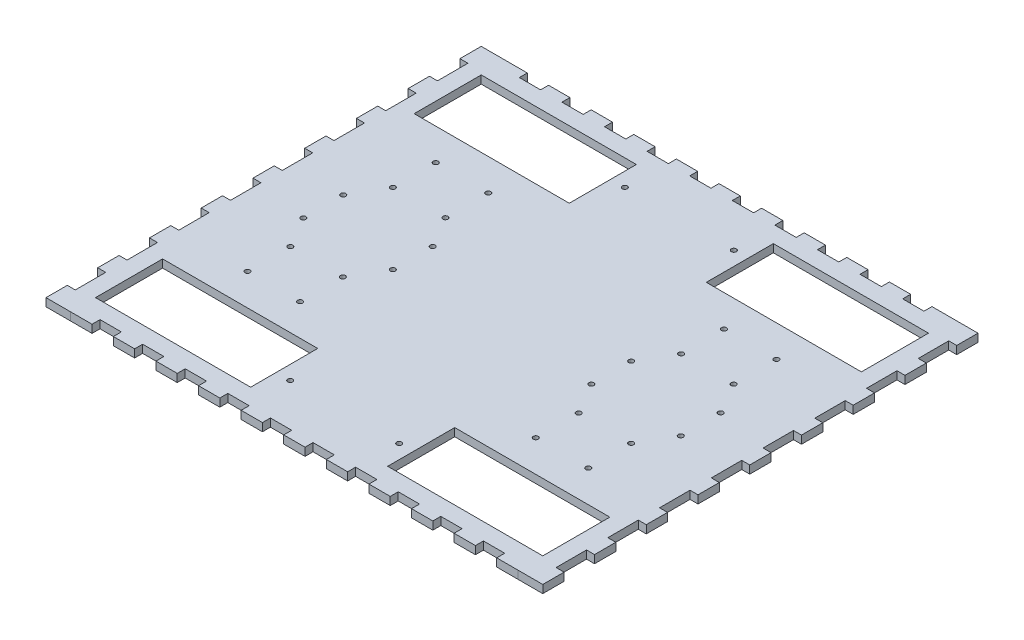
SolidWorks part; units mm, degrees
ref_plane "Front Plane" through (0, 0, 0) normal (0, 0, 1) x (1, 0, 0)
ref_plane "Top Plane" through (0, 0, 0) normal (0, 1, 0) x (1, 0, 0)
ref_plane "Right Plane" through (0, 0, 0) normal (1, 0, 0) x (0, 0, -1)
sketch "Sketch2" plane through (0, 0, 0) normal (0, 1, 0) x (1, 0, 0)
  line L11 (25.4, 125) -> (25.4, 129.7625)
  line L12 (12.7, -125) -> (25.4, -125)
  line L23 (0, -125) -> (0, 125)
  line L24 (12.7, 125) -> (25.4, 125)
  line L29 (266.7, -125) -> (266.7, 125)
  line L30 (25.4, 129.7625) -> (38.1, 129.7625)
  line L35 (38.1, 125) -> (38.1, 129.7625)
  line L41 (0, 125) -> (0, 129.7625)
  line L42 (0, 129.7625) -> (12.7, 129.7625)
  line L47 (12.7, 125) -> (12.7, 129.7625)
  line L48 (50.8, 125) -> (50.8, 129.7625)
  line L53 (50.8, 129.7625) -> (63.5, 129.7625)
  line L54 (63.5, 125) -> (63.5, 129.7625)
  line L59 (76.2, 125) -> (76.2, 129.7625)
  line L60 (76.2, 129.7625) -> (88.9, 129.7625)
  line L65 (88.9, 125) -> (88.9, 129.7625)
  line L66 (101.6, 125) -> (101.6, 129.7625)
  line L71 (101.6, 129.7625) -> (114.3, 129.7625)
  line L72 (114.3, 125) -> (114.3, 129.7625)
  line L77 (127, 125) -> (127, 129.7625)
  line L78 (127, 129.7625) -> (139.7, 129.7625)
  line L79 (139.7, 125) -> (139.7, 129.7625)
  line L80 (152.4, 125) -> (152.4, 129.7625)
  line L81 (152.4, 129.7625) -> (165.1, 129.7625)
  line L82 (165.1, 125) -> (165.1, 129.7625)
  line L83 (177.8, 125) -> (177.8, 129.7625)
  line L84 (177.8, 129.7625) -> (190.5, 129.7625)
  line L85 (190.5, 125) -> (190.5, 129.7625)
  line L86 (203.2, 125) -> (203.2, 129.7625)
  line L87 (203.2, 129.7625) -> (215.9, 129.7625)
  line L88 (215.9, 125) -> (215.9, 129.7625)
  line L89 (228.6, 125) -> (228.6, 129.7625)
  line L90 (228.6, 129.7625) -> (241.3, 129.7625)
  line L91 (241.3, 125) -> (241.3, 129.7625)
  line L92 (254, 125) -> (254, 129.7625)
  line L93 (254, 129.7625) -> (266.7, 129.7625)
  line L94 (266.7, 125) -> (266.7, 129.7625)
  line L95 (38.1, 125) -> (50.8, 125)
  line L96 (63.5, 125) -> (76.2, 125)
  line L97 (88.9, 125) -> (101.6, 125)
  line L98 (114.3, 125) -> (127, 125)
  line L99 (139.7, 125) -> (152.4, 125)
  line L100 (165.1, 125) -> (177.8, 125)
  line L101 (190.5, 125) -> (203.2, 125)
  line L102 (215.9, 125) -> (228.6, 125)
  line L103 (241.3, 125) -> (254, 125)
  line L104 (0, 0) -> (266.7, 0) construction
  line L105 (241.3, -125) -> (254, -125)
  line L106 (215.9, -125) -> (228.6, -125)
  line L107 (190.5, -125) -> (203.2, -125)
  line L108 (165.1, -125) -> (177.8, -125)
  line L109 (139.7, -125) -> (152.4, -125)
  line L110 (114.3, -125) -> (127, -125)
  line L111 (88.9, -125) -> (101.6, -125)
  line L112 (63.5, -125) -> (76.2, -125)
  line L113 (38.1, -125) -> (50.8, -125)
  line L114 (266.7, -125) -> (266.7, -129.7625)
  line L115 (254, -129.7625) -> (266.7, -129.7625)
  line L116 (254, -125) -> (254, -129.7625)
  line L117 (241.3, -125) -> (241.3, -129.7625)
  line L118 (228.6, -129.7625) -> (241.3, -129.7625)
  line L119 (228.6, -125) -> (228.6, -129.7625)
  line L120 (215.9, -125) -> (215.9, -129.7625)
  line L121 (203.2, -129.7625) -> (215.9, -129.7625)
  line L122 (203.2, -125) -> (203.2, -129.7625)
  line L123 (190.5, -125) -> (190.5, -129.7625)
  line L124 (177.8, -129.7625) -> (190.5, -129.7625)
  line L125 (177.8, -125) -> (177.8, -129.7625)
  line L126 (165.1, -125) -> (165.1, -129.7625)
  line L127 (152.4, -129.7625) -> (165.1, -129.7625)
  line L128 (152.4, -125) -> (152.4, -129.7625)
  line L129 (139.7, -125) -> (139.7, -129.7625)
  line L130 (127, -129.7625) -> (139.7, -129.7625)
  line L131 (127, -125) -> (127, -129.7625)
  line L132 (114.3, -125) -> (114.3, -129.7625)
  line L133 (101.6, -129.7625) -> (114.3, -129.7625)
  line L134 (101.6, -125) -> (101.6, -129.7625)
  line L135 (88.9, -125) -> (88.9, -129.7625)
  line L136 (76.2, -129.7625) -> (88.9, -129.7625)
  line L137 (76.2, -125) -> (76.2, -129.7625)
  line L138 (63.5, -125) -> (63.5, -129.7625)
  line L139 (50.8, -129.7625) -> (63.5, -129.7625)
  line L140 (50.8, -125) -> (50.8, -129.7625)
  line L141 (12.7, -125) -> (12.7, -129.7625)
  line L142 (0, -129.7625) -> (12.7, -129.7625)
  line L143 (0, -125) -> (0, -129.7625)
  line L144 (38.1, -125) -> (38.1, -129.7625)
  line L145 (25.4, -129.7625) -> (38.1, -129.7625)
  line L146 (12.7, -125) -> (25.4, -125)
  line L147 (25.4, -125) -> (25.4, -129.7625)
  line L148 (38.1, -125) -> (50.8, -125)
  line L149 (63.5, -125) -> (76.2, -125)
  line L150 (88.9, -125) -> (101.6, -125)
  line L151 (114.3, -125) -> (127, -125)
  line L152 (139.7, -125) -> (152.4, -125)
  line L153 (165.1, -125) -> (177.8, -125)
  line L154 (190.5, -125) -> (203.2, -125)
  line L155 (215.9, -125) -> (228.6, -125)
  line L156 (241.3, -125) -> (254, -125)
  point P68 (0, -129.7625)
  dimension "D1" = 250
  dimension "D2" = 266.7
  dimension "D3" = 12.7
  dimension "D4" = 4.7625
extrude "Boss-Extrude1" add sketch "Sketch2" along normal blind 4.7625 contours L12 L147 L145 L144 L113 L140 L139 L138 L112 L137 L136 L135 L111 L134 L133 L132 L110 L131 L130 L129 L109 L128 L127 L126 L108 L125 L124 L123 L107 L122 L121 L120 L106 L119 L118 L117 L105 L116 L115 L114 L29 L94 L93 L92 L103 L91 L90 L89 L102 L88 L87 | L23 L104 L29 L94 L93 L92 L103 L91 L90 L89 L102 L88 L87 L86 L101 L85 L84 L83 L100 L82 L81 L80 L99 L79 L78 L77 L98 L72 L71 L66 L97 L65 L60 L59 L96 L54 L53 L48 L95 L35 L30 L11 L24 L47 L42 L41
sketch "Sketch5" plane through (0, 4.7625, 0) normal (0, 1, 0) x (1, 0, 0)
  line L0 (100.85, 99.7625) -> (165.85, 99.7625) construction
  line L1 (25.4, 129.7625) -> (38.1, 129.7625) construction
  line L2 (100.85, -99.7625) -> (165.85, -99.7625) construction
  line L4 (127, 129.7625) -> (139.7, 129.7625) construction
  line L5 (0, 0) -> (266.7, 0) construction
  line L6 (0, -129.7625) -> (0, 129.7625) construction
  line L7 (266.7, 129.7625) -> (266.7, -129.7625) construction
  circle A0 centre (31.75, 56.1125) radius 1.5
  circle A1 centre (63.07, 56.1125) radius 1.5
  circle A2 centre (63.07, 30.5625) radius 1.5
  circle A3 centre (31.75, 30.5625) radius 1.5
  circle A20 centre (203.63, 56.1125) radius 1.5
  circle A21 centre (203.63, 30.5625) radius 1.5
  circle A22 centre (234.95, 30.5625) radius 1.5
  circle A23 centre (234.95, 56.1125) radius 1.5
  circle A24 centre (234.95, -56.1125) radius 1.5
  circle A25 centre (234.95, -30.5625) radius 1.5
  circle A26 centre (203.63, -30.5625) radius 1.5
  circle A27 centre (203.63, -56.1125) radius 1.5
  circle A28 centre (31.75, -30.5625) radius 1.5
  circle A29 centre (63.07, -30.5625) radius 1.5
  circle A30 centre (63.07, -56.1125) radius 1.5
  circle A31 centre (31.75, -56.1125) radius 1.5
  circle A32 centre (20.83, 11.885) radius 1.5
  circle A33 centre (74.17, 11.885) radius 1.5
  circle A34 centre (192.53, 11.885) radius 1.5
  circle A35 centre (245.87, 11.885) radius 1.5
  circle A36 centre (245.87, -11.885) radius 1.5
  circle A37 centre (192.53, -11.885) radius 1.5
  circle A38 centre (74.17, -11.885) radius 1.5
  circle A39 centre (20.83, -11.885) radius 1.5
  circle A40 centre (100.85, 99.7625) radius 1.5
  circle A41 centre (165.85, 99.7625) radius 1.5
  circle A42 centre (165.85, -99.7625) radius 1.5
  circle A43 centre (100.85, -99.7625) radius 1.5
  point P3 (64.57, 56.1125)
  point P7 (30.25, 56.1125)
  point P23 (31.75, 129.7625)
  point P50 (31.75, 57.6125)
  point P51 (31.75, 29.0625)
  point P69 (133.35, 99.7625)
  point P70 (133.35, 0)
  dimension "D1" = 28.55
  dimension "D3" = 3
  dimension "D4" = 2
  dimension "D12" = 3
  dimension "D2" = 18.6775
  dimension "D5" = 34.32
  dimension "D6" = 31.75
  dimension "D7" = 20.83
  dimension "D8" = 53.34
  dimension "D9" = 11.885
  dimension "D11" = 20.83
  dimension "D13" = 65
  dimension "D14" = 133.35
  dimension "D15" = 30
  dimension "D10" = 2
extrude "Cut-Extrude1" cut sketch "Sketch5" against normal through all
sketch "Sketch7" plane through (0, 4.7625, 0) normal (0, 1, 0) x (1, 0, 0)
  line L0 (0, 75) -> (92.5, 75)
  line L1 (0, -129.7625) -> (0, 129.7625) construction
  line L2 (92.5, 75) -> (92.5, 115)
  line L3 (92.5, 115) -> (0, 115)
  line L4 (0, 115) -> (0, 75)
  line L5 (0, 0) -> (266.7, 0) construction
  line L6 (266.7, 129.7625) -> (266.7, -129.7625) construction
  line L7 (133.35, 0) -> (133.35, 129.7625) construction
  line L8 (127, 129.7625) -> (139.7, 129.7625) construction
  line L9 (266.7, 115) -> (266.7, 75)
  line L10 (174.2, 115) -> (266.7, 115)
  line L11 (174.2, 75) -> (174.2, 115)
  line L12 (266.7, 75) -> (174.2, 75)
  line L13 (0, -115) -> (0, -75)
  line L14 (92.5, -115) -> (0, -115)
  line L15 (92.5, -75) -> (92.5, -115)
  line L16 (0, -75) -> (92.5, -75)
  line L17 (266.7, -75) -> (174.2, -75)
  line L18 (174.2, -75) -> (174.2, -115)
  line L19 (174.2, -115) -> (266.7, -115)
  line L20 (266.7, -115) -> (266.7, -75)
  dimension "D1" = 40
  dimension "D2" = 75
  dimension "D3" = 92.5
extrude "Cut-Extrude2" cut sketch "Sketch7" against normal through all
sketch "Sketch6" plane through (0, 4.7625, 0) normal (0, 1, 0) x (1, 0, 0)
  line L0 (0, -129.7625) -> (0, -115) construction
  line L1 (0, 129.7625) -> (12.7, 129.7625) construction
  line L2 (0, -75) -> (0, 75) construction
  text T0 "TREY MADE THIS CHASSIS\r\n the robot will be on this\r\n<i>      -\"Danny Devito\"</i>"
  text T1 "Calvin contributed"
  point P5 (106.6973, -5.2225)
  dimension "D1" = 101.6
  dimension "D2" = 82.677
  dimension "D3" = 106.6973
  dimension "D4" = 134.985
sketch "Sketch8" plane through (0, 4.7625, 0) normal (0, 1, 0) x (1, 0, 0)
  line L0 (0, -129.7625) -> (0, -115) construction
  line L1 (0, -129.76) -> (-10, -129.76)
  line L2 (0, -129.76) -> (0, 129.76)
  line L3 (0, 129.76) -> (-10, 129.76)
  line L4 (-10, -117.06) -> (-10, -98.9075)
  line L10 (-14.76, 98.9075) -> (-14.76, 86.2075)
  line L11 (-10, 129.76) -> (-14.76, 129.76)
  line L13 (-10, 117.06) -> (-14.76, 117.06)
  line L14 (-14.76, 129.76) -> (-14.76, 117.06)
  line L15 (-10, 86.2075) -> (-14.76, 86.2075)
  line L16 (-10, 98.9075) -> (-14.76, 98.9075)
  line L17 (-14.76, 68.055) -> (-14.76, 55.355)
  line L18 (-10, 55.355) -> (-14.76, 55.355)
  line L19 (-10, 68.055) -> (-14.76, 68.055)
  line L20 (-14.76, 37.2025) -> (-14.76, 24.5025)
  line L21 (-10, 24.5025) -> (-14.76, 24.5025)
  line L22 (-10, 37.2025) -> (-14.76, 37.2025)
  line L23 (-14.76, 6.35) -> (-14.76, -6.35)
  line L24 (-10, -6.35) -> (-14.76, -6.35)
  line L25 (-10, 6.35) -> (-14.76, 6.35)
  line L26 (-14.76, -24.5025) -> (-14.76, -37.2025)
  line L27 (-10, -37.2025) -> (-14.76, -37.2025)
  line L28 (-10, -24.5025) -> (-14.76, -24.5025)
  line L29 (-14.76, -55.355) -> (-14.76, -68.055)
  line L30 (-10, -68.055) -> (-14.76, -68.055)
  line L31 (-10, -55.355) -> (-14.76, -55.355)
  line L32 (-14.76, -86.2075) -> (-14.76, -98.9075)
  line L33 (-10, -98.9075) -> (-14.76, -98.9075)
  line L34 (-10, -86.2075) -> (-14.76, -86.2075)
  line L35 (-14.76, -117.06) -> (-14.76, -129.76)
  line L36 (-10, -129.76) -> (-14.76, -129.76)
  line L37 (-10, -117.06) -> (-14.76, -117.06)
  line L38 (133.35, 129.7625) -> (133.35, -129.7625) construction
  line L39 (127, 129.7625) -> (139.7, 129.7625) construction
  line L40 (127, -129.7625) -> (139.7, -129.7625) construction
  line L41 (-10, 98.9075) -> (-10, 117.06)
  line L42 (-10, 68.055) -> (-10, 86.2075)
  line L43 (-10, 37.2025) -> (-10, 55.355)
  line L44 (-10, 6.35) -> (-10, 24.5025)
  line L45 (-10, -24.5025) -> (-10, -6.35)
  line L46 (-10, -55.355) -> (-10, -37.2025)
  line L47 (-10, -86.2075) -> (-10, -68.055)
  line L48 (276.7, -86.2075) -> (276.7, -68.055)
  line L49 (276.7, -55.355) -> (276.7, -37.2025)
  line L50 (276.7, -24.5025) -> (276.7, -6.35)
  line L51 (276.7, 6.35) -> (276.7, 24.5025)
  line L52 (276.7, 37.2025) -> (276.7, 55.355)
  line L53 (276.7, 68.055) -> (276.7, 86.2075)
  line L54 (276.7, 98.9075) -> (276.7, 117.06)
  line L55 (276.7, -117.06) -> (281.46, -117.06)
  line L56 (276.7, -129.76) -> (281.46, -129.76)
  line L57 (281.46, -117.06) -> (281.46, -129.76)
  line L58 (276.7, -86.2075) -> (281.46, -86.2075)
  line L59 (276.7, -98.9075) -> (281.46, -98.9075)
  line L60 (281.46, -86.2075) -> (281.46, -98.9075)
  line L61 (276.7, -55.355) -> (281.46, -55.355)
  line L62 (276.7, -68.055) -> (281.46, -68.055)
  line L63 (281.46, -55.355) -> (281.46, -68.055)
  line L64 (276.7, -24.5025) -> (281.46, -24.5025)
  line L65 (276.7, -37.2025) -> (281.46, -37.2025)
  line L66 (281.46, -24.5025) -> (281.46, -37.2025)
  line L67 (276.7, 6.35) -> (281.46, 6.35)
  line L68 (276.7, -6.35) -> (281.46, -6.35)
  line L69 (281.46, 6.35) -> (281.46, -6.35)
  line L70 (276.7, 37.2025) -> (281.46, 37.2025)
  line L71 (276.7, 24.5025) -> (281.46, 24.5025)
  line L72 (281.46, 37.2025) -> (281.46, 24.5025)
  line L73 (276.7, 68.055) -> (281.46, 68.055)
  line L74 (276.7, 55.355) -> (281.46, 55.355)
  line L75 (281.46, 68.055) -> (281.46, 55.355)
  line L76 (276.7, 98.9075) -> (281.46, 98.9075)
  line L77 (276.7, 86.2075) -> (281.46, 86.2075)
  line L78 (281.46, 129.76) -> (281.46, 117.06)
  line L79 (276.7, 117.06) -> (281.46, 117.06)
  line L80 (276.7, 129.76) -> (281.46, 129.76)
  line L81 (281.46, 98.9075) -> (281.46, 86.2075)
  line L82 (276.7, -117.06) -> (276.7, -98.9075)
  line L83 (266.7, 129.76) -> (276.7, 129.76)
  line L84 (266.7, -129.76) -> (266.7, 129.76)
  line L85 (266.7, -129.76) -> (276.7, -129.76)
  dimension "D1" = 10
  dimension "D3" = 129.76
  dimension "D4" = 129.76
  dimension "D7" = 12.7
  dimension "D8" = 4.76
  dimension "D9" = 9
extrude "Boss-Extrude2" add sketch "Sketch8" along direction (0, 1, 0) on the side against the normal up to surface (4.7625 mm away) contours L34 L32 L33
